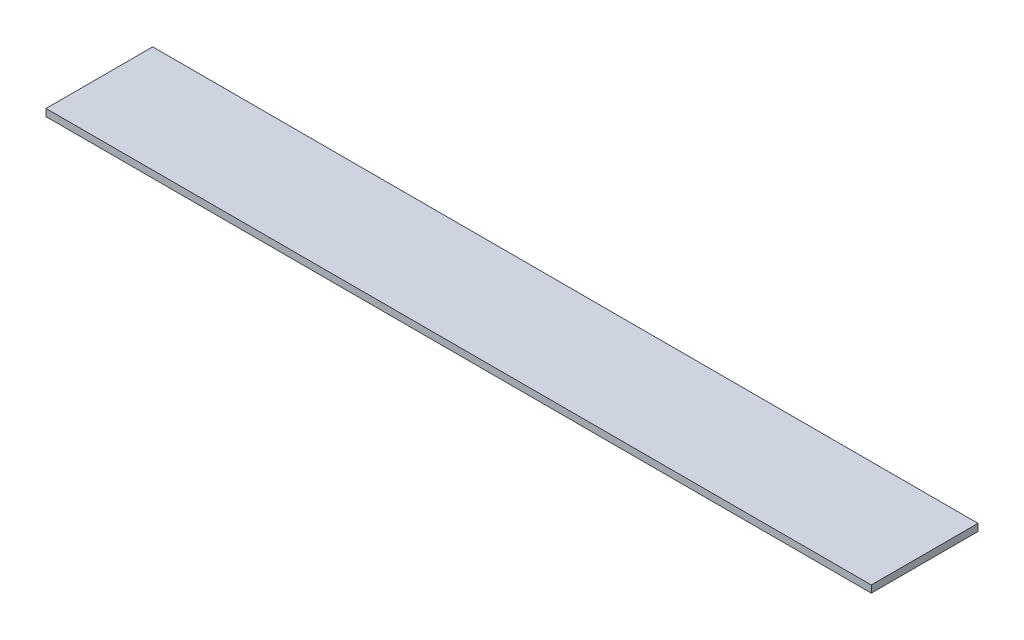
SolidWorks part; units mm, degrees
ref_plane "Front Plane" through (0, 0, 0) normal (0, 0, 1) x (1, 0, 0)
ref_plane "Top Plane" through (0, 0, 0) normal (0, 1, 0) x (1, 0, 0)
ref_plane "Right Plane" through (0, 0, 0) normal (1, 0, 0) x (0, 0, -1)
sketch "Sketch1" plane through (0, 0, 0) normal (0, 1, 0) x (1, 0, 0)
  line L1 (-290, 37.5) -> (290, 37.5)
  line L2 (-290, 37.5) -> (-290, -37.5)
  line L3 (-290, -37.5) -> (290, -37.5)
  line L4 (290, 37.5) -> (290, -37.5)
  point P4 (0, -37.5)
  point P6 (290, 0)
  dimension "D1" = 580
  dimension "D2" = 75
extrude "Boss-Extrude1" add sketch "Sketch1" along normal blind 5
